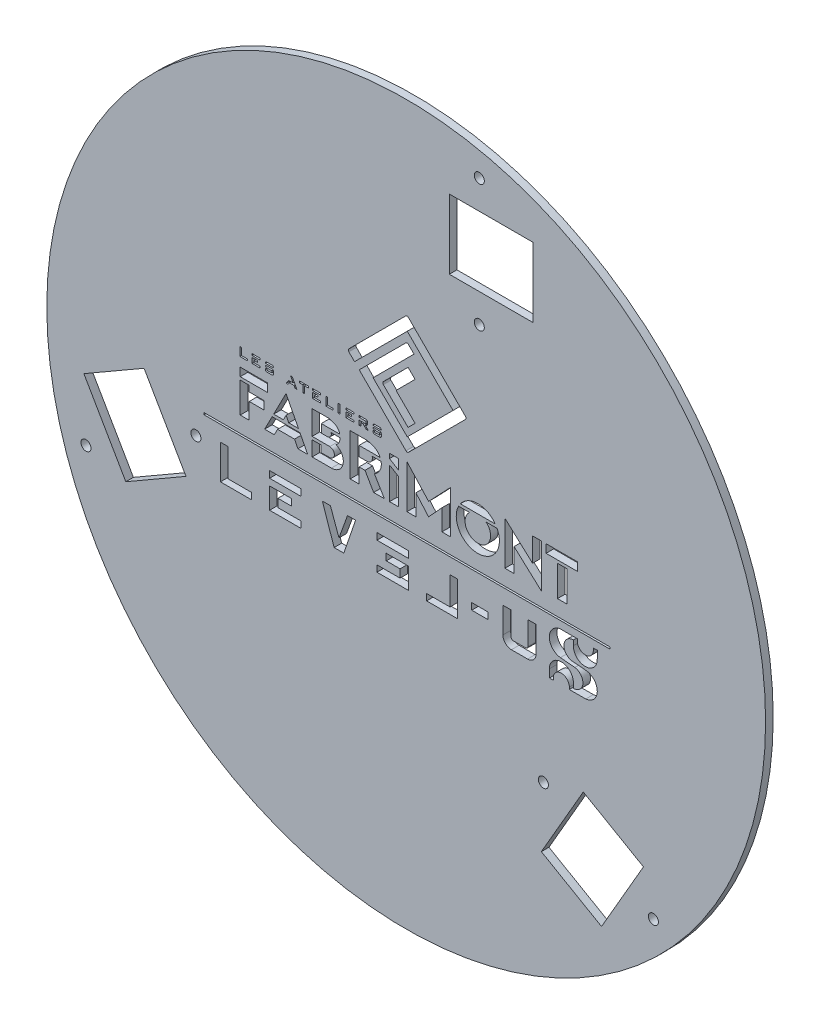
SolidWorks part; units mm, degrees
material "201 Acier inoxydable recuit (SS)"
ref_plane "Plan de face" through (0, 0, 0) normal (0, 0, 1) x (1, 0, 0)
ref_plane "Plan de dessus" through (0, 0, 0) normal (0, 1, 0) x (1, 0, 0)
ref_plane "Plan de droite" through (0, 0, 0) normal (1, 0, 0) x (0, 0, -1)
sketch "Esquisse1" plane through (0, 0, 0) normal (0, 0, 1) x (1, 0, 0)
  line B0 (39.8028, 108.2692) -> (61.818, 130.2872)
  line B1 (61.818, 130.2872) -> (80.9149, 111.1927)
  line B2 (86.1174, 111.6371) -> (62.256, 135.4954)
  circle B3 centre (61.368, 63.9273) radius 150
  line B4 (88.7074, 42.8985) -> (95.439, 42.8985)
  line B5 (95.439, 45.6563) -> (95.439, 42.8985)
  line B6 (88.7074, 45.6563) -> (95.439, 45.6563)
  line B7 (88.7074, 45.6563) -> (88.7074, 42.8985)
  line B8 (69.9017, 36.8558) -> (69.9017, 39.5372)
  line B9 (82.771, 36.8558) -> (69.9017, 36.8558)
  line B10 (82.771, 51.2103) -> (82.771, 36.8558)
  line B11 (79.6565, 51.2103) -> (82.771, 51.2103)
  line B12 (79.6565, 39.5372) -> (79.6565, 51.2103)
  line B13 (69.9017, 39.5372) -> (79.6565, 39.5372)
  line B14 (49.1501, 51.2103) -> (49.1501, 48.4256)
  line B15 (62.241, 48.4256) -> (49.1501, 48.4256)
  line B16 (62.241, 51.2103) -> (62.241, 48.4256)
  line B17 (62.241, 51.2103) -> (49.1501, 51.2103)
  line B18 (4.3716, 48.4256) -> (17.4625, 48.4256)
  line B19 (17.4625, 51.1933) -> (17.4625, 48.4256)
  line B20 (4.3716, 51.1933) -> (17.4625, 51.1933)
  line B21 (4.3716, 51.1933) -> (4.3716, 48.4256)
  line B22 (4.3716, 36.8558) -> (17.4625, 36.8558)
  line B23 (17.4625, 39.5291) -> (17.4625, 36.8558)
  line B24 (7.8145, 39.5291) -> (17.4625, 39.5291)
  line B25 (7.8145, 42.8985) -> (7.8145, 39.5291)
  line B26 (7.8145, 42.8985) -> (13.5765, 42.8985)
  line B27 (13.5765, 45.6563) -> (13.5765, 42.8985)
  line B28 (4.3716, 45.6563) -> (13.5765, 45.6563)
  line B29 (4.3716, 45.6563) -> (4.3716, 36.8558)
  line B30 (48.2118, 89.8237) -> (50.3046, 89.8237)
  line B31 (47.526, 89.1379) -> (47.526, 89.1275)
  line B32 (47.526, 89.1275) -> (50.9904, 89.1275)
  line B33 (50.9904, 89.1379) -> (50.9904, 89.1275)
  line B34 (36.2507, 89.8237) -> (36.2507, 89.1275)
  line B35 (39.5235, 89.1275) -> (36.2507, 89.1275)
  line B36 (39.5235, 89.8237) -> (39.5235, 89.1275)
  line B37 (36.2507, 89.8237) -> (39.5235, 89.8237)
  line B38 (27.7962, 86.2351) -> (30.9007, 86.2351)
  line B39 (30.9007, 86.9054) -> (30.9007, 86.2351)
  line B40 (28.4753, 86.9054) -> (30.9007, 86.9054)
  line B41 (28.4753, 89.8237) -> (28.4753, 86.9054)
  line B42 (27.7962, 89.8237) -> (28.4753, 89.8237)
  line B43 (27.7962, 89.8237) -> (27.7962, 86.2351)
  line B44 (32.9588, 86.2351) -> (33.6448, 86.2351)
  line B45 (33.6448, 89.8237) -> (33.6448, 86.2351)
  line B46 (32.9588, 89.8237) -> (33.6448, 89.8237)
  line B47 (32.9588, 89.8237) -> (32.9588, 86.2351)
  line B48 (24.5672, 88.4352) -> (24.5672, 87.7457)
  line B49 (22.266, 88.4352) -> (24.5672, 88.4352)
  line B50 (22.266, 88.4352) -> (22.266, 86.2351)
  line B51 (22.266, 86.2351) -> (25.5387, 86.2351)
  line B52 (25.5387, 86.9054) -> (25.5387, 86.2351)
  line B53 (23.1267, 86.9054) -> (25.5387, 86.9054)
  line B54 (23.1267, 87.7457) -> (23.1267, 86.9054)
  line B55 (23.1267, 87.7457) -> (24.5672, 87.7457)
  line B56 (22.266, 89.1275) -> (25.5387, 89.1275)
  line B57 (25.5387, 89.8237) -> (25.5387, 89.1275)
  line B58 (22.266, 89.8237) -> (25.5387, 89.8237)
  line B59 (22.266, 89.8237) -> (22.266, 89.1275)
  line B60 (-2.0636, 87.7457) -> (-0.6231, 87.7457)
  line B61 (-0.6231, 88.4352) -> (-0.6231, 87.7457)
  line B62 (-2.9243, 88.4352) -> (-0.6231, 88.4352)
  line B63 (-2.9243, 88.4352) -> (-2.9243, 86.2351)
  line B64 (-2.9243, 86.2351) -> (0.3484, 86.2351)
  line B65 (0.3484, 86.9034) -> (0.3484, 86.2351)
  line B66 (-2.0636, 86.9034) -> (0.3484, 86.9034)
  line B67 (-2.0636, 87.7457) -> (-2.0636, 86.9034)
  line B68 (-2.9243, 89.1275) -> (0.3484, 89.1275)
  line B69 (0.3484, 89.8237) -> (0.3484, 89.1275)
  line B70 (-2.9243, 89.8237) -> (0.3484, 89.8237)
  line B71 (-2.9243, 89.8237) -> (-2.9243, 89.1275)
  line B72 (62.1432, 95.6886) -> (51.8218, 105.9912)
  line B73 (65.0775, 98.6282) -> (62.1432, 95.6886)
  line B74 (57.1433, 106.5614) -> (65.0775, 98.6282)
  line B75 (65.0725, 114.505) -> (57.1433, 106.5614)
  line B76 (62.1527, 117.4195) -> (65.0725, 114.505)
  line B77 (51.8208, 107.0689) -> (62.1527, 117.4195)
  line B78 (3.2629, 86.2351) -> (5.3557, 86.2351)
  line B79 (6.0415, 87.7494) -> (6.0415, 86.9209)
  line B80 (2.5771, 88.4352) -> (5.3557, 88.4352)
  line B81 (2.5771, 88.4352) -> (2.5771, 88.4315)
  line B82 (3.2629, 87.7457) -> (5.3557, 87.7457)
  line B83 (5.3557, 87.7457) -> (5.3557, 86.9034)
  line B84 (3.2653, 86.9034) -> (5.3557, 86.9034)
  line B85 (3.2653, 87.3351) -> (3.2653, 86.9034)
  line B86 (2.5771, 87.3351) -> (3.2653, 87.3351)
  line B87 (2.5771, 86.9209) -> (2.5771, 87.3351)
  line B88 (20.5559, 89.8237) -> (20.5559, 89.1275)
  line B89 (16.7521, 89.8237) -> (20.5559, 89.8237)
  line B90 (16.7521, 89.8237) -> (16.7521, 89.1275)
  line B91 (16.7521, 89.1275) -> (18.2994, 89.1275)
  line B92 (18.2994, 89.1275) -> (18.2994, 86.2351)
  line B93 (18.2994, 86.2351) -> (18.9764, 86.2351)
  line B94 (18.9764, 89.1275) -> (18.9764, 86.2351)
  line B95 (18.9764, 89.1275) -> (20.5559, 89.1275)
  line B96 (54.4137, 80.5603) -> (58.1808, 78.2403)
  line B97 (58.1808, 78.2403) -> (58.1808, 82.4618)
  line B98 (54.4137, 82.4618) -> (58.1808, 82.4618)
  line B99 (54.4137, 82.4618) -> (54.4137, 80.5603)
  line B100 (65.4199, 73.6995) -> (65.4199, 64.9856)
  line B101 (70.7111, 67.6307) -> (65.4199, 73.6995)
  line B102 (76.2673, 73.6995) -> (70.7111, 67.6307)
  line B103 (76.2673, 64.9856) -> (76.2673, 73.6995)
  line B104 (79.8874, 64.9856) -> (76.2673, 64.9856)
  line B105 (79.8874, 82.8613) -> (79.8874, 64.9856)
  line B106 (70.7197, 73.2332) -> (79.8874, 82.8613)
  line B107 (61.6887, 83.0856) -> (70.7197, 73.2332)
  line B108 (61.6887, 64.9856) -> (61.6887, 83.0856)
  line B109 (61.6887, 64.9856) -> (65.4199, 64.9856)
  line B110 (94.707, 77.7674) -> (99.3064, 77.7674)
  line B111 (83.2222, 77.7674) -> (87.8216, 77.7674)
  line B112 (-23.0062, 57.679) -> (146.3836, 57.679)
  line B113 (146.3836, 58.4778) -> (146.3836, 57.679)
  line B114 (-23.0062, 58.4778) -> (146.3836, 58.4778)
  line B115 (-23.0062, 58.4778) -> (-23.0062, 57.679)
  line B116 (124.5042, 64.9856) -> (128.4237, 64.9856)
  line B117 (128.4237, 77.7674) -> (128.4237, 64.9856)
  line B118 (124.5042, 77.7674) -> (128.4237, 77.7674)
  line B119 (124.5042, 64.9856) -> (124.5042, 77.7674)
  line B120 (119.7421, 78.9781) -> (132.9293, 78.9781)
  line B121 (132.9293, 78.9781) -> (132.9293, 82.4618)
  line B122 (119.7421, 82.4618) -> (132.9293, 82.4618)
  line B123 (119.7421, 82.4618) -> (119.7421, 78.9781)
  line B124 (11.2269, 82.4618) -> (16.4081, 72.4291)
  line B125 (6.0539, 72.4291) -> (11.2269, 82.4618)
  line B126 (6.0539, 72.4291) -> (10.1027, 72.4291)
  line B127 (11.2269, 74.6095) -> (10.1027, 72.4291)
  line B128 (12.3529, 72.4291) -> (11.2269, 74.6095)
  line B129 (12.3529, 72.4291) -> (16.4081, 72.4291)
  line B130 (2.0157, 71.9118) -> (-4.1611, 71.9118)
  line B131 (2.0157, 75.3461) -> (2.0157, 71.9118)
  line B132 (-4.1611, 75.3461) -> (2.0157, 75.3461)
  line B133 (-4.1611, 77.7674) -> (-4.1611, 75.3461)
  line B134 (-7.9167, 77.7674) -> (-4.1611, 77.7674)
  line B135 (-7.9167, 65.1187) -> (-7.9167, 77.7674)
  line B136 (-4.1611, 65.1187) -> (-7.9167, 65.1187)
  line B137 (-4.1611, 71.9118) -> (-4.1611, 65.1187)
  line B138 (47.526, 88.4352) -> (50.3046, 88.4352)
  line B139 (47.526, 88.4352) -> (47.526, 88.4315)
  line B140 (48.2118, 87.7457) -> (50.3046, 87.7457)
  line B141 (50.3046, 87.7457) -> (50.3046, 86.9034)
  line B142 (48.2142, 86.9034) -> (50.3046, 86.9034)
  line B143 (48.2142, 87.3351) -> (48.2142, 86.9034)
  line B144 (47.526, 87.3351) -> (48.2142, 87.3351)
  line B145 (47.526, 86.9209) -> (47.526, 87.3351)
  line B146 (48.2118, 86.2351) -> (50.3046, 86.2351)
  line B147 (50.9904, 87.7494) -> (50.9904, 86.9209)
  line B148 (2.2846, 65.1187) -> (6.3334, 65.1187)
  line B149 (7.6996, 67.7684) -> (6.3334, 65.1187)
  line B150 (7.6996, 67.7684) -> (14.7598, 67.7684)
  line B151 (16.1969, 64.9856) -> (14.7598, 67.7684)
  line B152 (20.2521, 64.9856) -> (16.1969, 64.9856)
  line B153 (17.0426, 71.2005) -> (20.2521, 64.9856)
  line B154 (5.4205, 71.2005) -> (17.0426, 71.2005)
  line B155 (2.2846, 65.1187) -> (5.4205, 71.2005)
  line B156 (25.9311, 78.9782) -> (33.6797, 78.9782)
  line B157 (30.831, 81.9696) -> (29.2994, 82.4619)
  line B158 (22.1049, 82.4619) -> (29.2994, 82.4619)
  line B159 (22.1049, 82.4619) -> (22.1049, 72.4292)
  line B160 (22.1049, 72.4292) -> (29.4781, 72.4292)
  line B161 (25.9038, 68.4321) -> (29.3823, 68.4321)
  line B162 (25.9038, 71.2006) -> (25.9038, 68.4321)
  line B163 (22.1049, 71.2006) -> (25.9038, 71.2006)
  line B164 (22.1049, 71.2006) -> (22.1049, 64.9857)
  line B165 (22.1049, 64.9857) -> (30.1503, 64.9857)
  line B166 (30.0311, 77.7675) -> (33.8261, 77.7675)
  line B167 (25.9311, 75.5023) -> (28.6488, 75.5023)
  line B168 (25.9311, 78.9782) -> (25.9311, 75.5023)
  line B169 (41.7054, 78.9781) -> (50.4924, 78.9781)
  line B170 (47.1354, 81.9098) -> (45.198, 82.4618)
  line B171 (37.9796, 82.4618) -> (45.198, 82.4618)
  line B172 (37.9796, 82.4618) -> (37.9796, 64.9856)
  line B173 (37.9796, 64.9856) -> (41.7054, 64.9856)
  line B174 (41.7054, 64.9856) -> (41.7054, 71.2005)
  line B175 (41.7054, 71.2005) -> (44.1723, 71.2005)
  line B176 (44.1723, 71.2005) -> (47.7793, 64.9856)
  line B177 (47.7793, 64.9856) -> (52.2442, 64.9856)
  line B178 (52.2442, 64.9856) -> (48.0671, 71.9455)
  line B179 (47.1354, 77.7675) -> (50.8798, 77.7675)
  line B180 (41.7054, 74.8449) -> (45.0294, 74.8449)
  line B181 (41.7054, 78.9781) -> (41.7054, 74.8449)
  line B182 (-73.1498, 47.4625) -> (-55.6498, 17.1516)
  line B183 (-55.6498, 17.1516) -> (-30.5351, 31.6516)
  line B184 (-30.5351, 31.6516) -> (-48.0351, 61.9625)
  line B185 (-48.0351, 61.9625) -> (-73.1498, 47.4625)
  line B186 (135.271, 0.4747) -> (117.771, -29.8362)
  line B187 (117.771, -29.8362) -> (142.8858, -44.3362)
  line B188 (142.8858, -44.3362) -> (160.3858, -14.0253)
  line B189 (160.3858, -14.0253) -> (135.271, 0.4747)
  line B190 (79.368, 159.6555) -> (114.368, 159.6555)
  line B191 (114.368, 159.6555) -> (114.368, 188.6555)
  line B192 (114.368, 188.6555) -> (79.368, 188.6555)
  line B193 (79.368, 188.6555) -> (79.368, 159.6555)
  line B194 (61.2027, 125.7562) -> (41.7606, 106.3116)
  line B195 (61.2791, 86.7956) -> (41.7606, 106.3116)
  line B196 (62.3568, 86.7957) -> (86.1175, 110.5594)
  line B197 (37.4177, 111.7316) -> (61.1784, 135.4953)
  line B198 (39.8028, 108.2692) -> (37.4178, 110.6539)
  line B199 (80.9149, 111.1927) -> (61.818, 92.0934)
  line B200 (61.818, 92.0934) -> (47.5628, 106.3468)
  line B201 (47.5628, 106.3468) -> (64.6253, 123.4115)
  line B202 (64.6253, 123.4115) -> (62.2803, 125.7562)
  line B203 (54.4137, 64.9856) -> (58.1808, 64.9856)
  line B204 (58.1808, 75.9434) -> (58.1808, 64.9856)
  line B205 (54.4137, 78.2403) -> (58.1808, 75.9434)
  line B206 (54.4137, 78.2403) -> (54.4137, 64.9856)
  line B207 (3.4734, 82.4618) -> (-7.9167, 82.4618)
  line B208 (-7.9167, 82.4618) -> (-7.9167, 78.9781)
  line B209 (-7.9167, 78.9781) -> (3.4734, 78.9781)
  line B210 (3.4734, 78.9781) -> (3.4734, 82.4618)
  line B211 (102.5461, 64.9856) -> (106.3956, 64.9856)
  line B212 (106.3956, 74.7482) -> (106.3956, 64.9856)
  line B213 (117.8763, 64.2748) -> (106.3956, 74.7482)
  line B214 (117.8763, 82.4618) -> (117.8763, 64.2748)
  line B215 (114.108, 82.4618) -> (117.8763, 82.4618)
  line B216 (114.108, 82.4618) -> (114.108, 72.5572)
  line B217 (114.108, 72.5572) -> (102.5461, 83.0856)
  line B218 (102.5461, 83.0856) -> (102.5461, 64.9856)
  line B219 (83.9595, 78.9781) -> (98.5691, 78.9781)
  line B220 (14.5348, 87.0641) -> (14.9597, 86.2351)
  line B221 (14.9597, 86.2351) -> (15.7483, 86.2351)
  line B222 (13.8053, 89.8237) -> (15.7483, 86.2351)
  line B223 (13.1204, 89.8237) -> (13.8053, 89.8237)
  line B224 (13.1204, 89.8237) -> (14.1854, 87.7457)
  line B225 (12.2814, 87.7457) -> (14.1854, 87.7457)
  line B226 (11.3422, 86.2351) -> (12.2814, 87.7457)
  line B227 (11.3422, 86.2351) -> (12.0777, 86.2351)
  line B228 (12.0777, 86.2351) -> (12.5628, 87.0641)
  line B229 (12.5628, 87.0641) -> (14.5348, 87.0641)
  line B230 (3.2629, 89.8237) -> (5.3557, 89.8237)
  line B231 (2.5771, 89.1379) -> (2.5771, 89.1275)
  line B232 (2.5771, 89.1275) -> (6.0415, 89.1275)
  line B233 (-7.2782, 89.8237) -> (-8.0568, 89.8237)
  line B234 (-8.0568, 89.8237) -> (-8.0568, 86.2351)
  line B235 (-8.0568, 86.2351) -> (-4.8395, 86.2351)
  line B236 (-4.8395, 86.2351) -> (-4.8395, 86.9054)
  line B237 (-4.8395, 86.9054) -> (-7.2782, 86.9054)
  line B238 (-7.2782, 86.9054) -> (-7.2782, 89.8237)
  line B239 (36.2507, 86.2351) -> (39.5235, 86.2351)
  line B240 (39.5235, 86.9054) -> (39.5235, 86.2351)
  line B241 (37.1115, 86.9054) -> (39.5235, 86.9054)
  line B242 (37.1115, 87.7457) -> (37.1115, 86.9054)
  line B243 (37.1115, 87.7457) -> (38.552, 87.7457)
  line B244 (38.552, 88.4352) -> (38.552, 87.7457)
  line B245 (36.2507, 88.4352) -> (38.552, 88.4352)
  line B246 (36.2507, 88.4352) -> (36.2507, 86.2351)
  line B247 (45.1742, 89.1379) -> (45.1742, 88.2688)
  line B248 (41.7675, 89.8237) -> (44.4884, 89.8237)
  line B249 (41.7675, 89.8237) -> (41.7675, 89.1275)
  line B250 (41.7675, 89.1275) -> (44.51, 89.1275)
  line B251 (44.51, 89.1275) -> (44.51, 88.1035)
  line B252 (41.7675, 88.1035) -> (44.51, 88.1035)
  line B253 (41.7675, 88.1035) -> (41.7675, 86.2351)
  line B254 (41.7675, 86.2351) -> (42.5631, 86.2351)
  line B255 (42.5631, 86.2351) -> (42.5631, 87.5734)
  line B256 (42.5631, 87.5734) -> (43.3631, 87.5734)
  line B257 (43.3631, 87.5734) -> (44.6642, 86.2351)
  line B258 (44.6642, 86.2351) -> (45.6087, 86.2351)
  line B259 (44.2011, 87.583) -> (45.6087, 86.2351)
  line B260 (44.2011, 87.583) -> (44.4884, 87.583)
  line B261 (31.2817, 36.8388) -> (35.3306, 36.8388)
  line B262 (40.235, 51.1933) -> (35.3306, 36.8388)
  line B263 (40.235, 51.1933) -> (36.8744, 51.1933)
  line B264 (36.8744, 51.1933) -> (33.3061, 41.3238)
  line B265 (29.7378, 51.1933) -> (33.3061, 41.3238)
  line B266 (26.3773, 51.1933) -> (29.7378, 51.1933)
  line B267 (26.3773, 51.1933) -> (31.2817, 36.8388)
  line B268 (-3.2891, 39.5372) -> (-13.0439, 39.5372)
  line B269 (-13.0439, 39.5372) -> (-13.0439, 51.2103)
  line B270 (-13.0439, 51.2103) -> (-16.1585, 51.2103)
  line B271 (-16.1585, 51.2103) -> (-16.1585, 36.8558)
  line B272 (-16.1585, 36.8558) -> (-3.2891, 36.8558)
  line B273 (-3.2891, 36.8558) -> (-3.2891, 39.5372)
  line B274 (49.1501, 39.5291) -> (49.1501, 36.8558)
  line B275 (62.241, 36.8558) -> (49.1501, 36.8558)
  line B276 (62.241, 45.6563) -> (62.241, 36.8558)
  line B277 (62.241, 45.6563) -> (53.0361, 45.6563)
  line B278 (53.0361, 45.6563) -> (53.0361, 42.8985)
  line B279 (58.7981, 42.8985) -> (53.0361, 42.8985)
  line B280 (58.7981, 42.8985) -> (58.7981, 39.5291)
  line B281 (58.7981, 39.5291) -> (49.1501, 39.5291)
  line B282 (115.5796, 40.4674) -> (115.5796, 51.2103)
  line B283 (115.5796, 51.2103) -> (112.2191, 51.2103)
  line B284 (112.2191, 51.2103) -> (112.2191, 41.5374)
  line B285 (111.2031, 40.5214) -> (106.0985, 40.5214)
  line B286 (105.0825, 51.2103) -> (105.0825, 41.5374)
  line B287 (101.7219, 51.2103) -> (105.0825, 51.2103)
  line B288 (101.7219, 51.2103) -> (101.7219, 40.4674)
  line B289 (105.2779, 36.9114) -> (112.0236, 36.9114)
  line B290 (121.1489, 34.6087) -> (121.1197, 37.9245)
  line B291 (122.7583, 34.6087) -> (121.1489, 34.6087)
  line B292 (122.7583, 35.4712) -> (122.7583, 34.6087)
  line B293 (129.4604, 35.4712) -> (129.4604, 34.6087)
  line B294 (136.3117, 34.6087) -> (129.4604, 34.6087)
  line B295 (130.5575, 45.4514) -> (136.1173, 45.0077)
  line B296 (131.1263, 53.3642) -> (131.1165, 51.2484)
  line B297 (141.1491, 54.6249) -> (141.0994, 51.2484)
  line B298 (141.1491, 54.6249) -> (139.4593, 54.6249)
  line B299 (139.4593, 53.784) -> (139.4593, 54.6249)
  line B300 (132.7753, 53.784) -> (132.7753, 54.6249)
  line B301 (132.7753, 54.6249) -> (125.6999, 54.6249)
  line B302 (125.6999, 44.2672) -> (131.7548, 43.7322)
  line B303 (131.1263, 35.8751) -> (131.1495, 37.9245)
  arc B304 (-24.2928, 48.4769) -> (-28.4928, 48.4769) centre (-26.3928, 48.4769) ccw
  arc B305 (-28.4928, 48.4769) -> (-24.2928, 48.4769) centre (-26.3928, 48.4769) ccw
  arc B306 (-70.1921, 21.9769) -> (-74.3921, 21.9769) centre (-72.2921, 21.9769) ccw
  arc B307 (-74.3921, 21.9769) -> (-70.1921, 21.9769) centre (-72.2921, 21.9769) ccw
  arc B308 (120.7287, -4.3506) -> (116.5287, -4.3506) centre (118.6287, -4.3506) ccw
  arc B309 (116.5287, -4.3506) -> (120.7287, -4.3506) centre (118.6287, -4.3506) ccw
  arc B310 (166.6281, -30.8506) -> (162.4281, -30.8506) centre (164.5281, -30.8506) ccw
  arc B311 (162.4281, -30.8506) -> (166.6281, -30.8506) centre (164.5281, -30.8506) ccw
  arc B312 (89.768, 147.6555) -> (93.968, 147.6555) centre (91.868, 147.6555) ccw
  arc B313 (93.968, 147.6555) -> (89.768, 147.6555) centre (91.868, 147.6555) ccw
  arc B314 (93.968, 200.6555) -> (89.768, 200.6555) centre (91.868, 200.6555) ccw
  arc B315 (89.768, 200.6555) -> (93.968, 200.6555) centre (91.868, 200.6555) ccw
  arc B316 (48.2118, 89.8237) -> (47.526, 89.1379) centre (48.2118, 89.1379) ccw
  arc B317 (50.9904, 89.1379) -> (50.3046, 89.8237) centre (50.3046, 89.1379) ccw
  arc B318 (51.8208, 107.0689) -> (51.8218, 105.9912) centre (52.3601, 106.5305) ccw
  arc B319 (5.3557, 86.2351) -> (6.0415, 86.9209) centre (5.3557, 86.9209) ccw
  arc B320 (6.0415, 87.7494) -> (5.3557, 88.4352) centre (5.3557, 87.7494) ccw
  arc B321 (2.5771, 88.4315) -> (3.2629, 87.7457) centre (3.2629, 88.4315) ccw
  arc B322 (2.5771, 86.9209) -> (3.2629, 86.2351) centre (3.2629, 86.9209) ccw
  arc B323 (87.8216, 77.7674) -> (94.707, 77.7674) centre (91.2643, 73.6995) ccw
  arc B324 (83.2222, 77.7674) -> (99.3064, 77.7674) centre (91.2643, 73.6995) ccw
  arc B325 (47.526, 88.4315) -> (48.2118, 87.7457) centre (48.2118, 88.4315) ccw
  arc B326 (47.526, 86.9209) -> (48.2118, 86.2351) centre (48.2118, 86.9209) ccw
  arc B327 (50.3046, 86.2351) -> (50.9904, 86.9209) centre (50.3046, 86.9209) ccw
  arc B328 (50.9904, 87.7494) -> (50.3046, 88.4352) centre (50.3046, 87.7494) ccw
  arc B329 (33.6797, 78.9782) -> (30.831, 81.9696) centre (29.5101, 77.8597) ccw
  arc B330 (29.3823, 68.4321) -> (29.4781, 72.4292) centre (29.3823, 70.4318) ccw
  arc B331 (30.1503, 64.9857) -> (32.1241, 74.4241) centre (30.2166, 69.8974) ccw
  arc B332 (32.1241, 74.4241) -> (33.8261, 77.7675) centre (29.5101, 77.8597) ccw
  arc B333 (28.6488, 75.5023) -> (30.0311, 77.7675) centre (28.3824, 77.2192) ccw
  arc B334 (50.4924, 78.9781) -> (47.1354, 81.9098) centre (45.578, 76.7384) ccw
  arc B335 (48.0671, 71.9455) -> (50.8798, 77.7675) centre (45.578, 76.7384) ccw
  arc B336 (45.0294, 74.8449) -> (47.1354, 77.7675) centre (45.0294, 77.065) ccw
  arc B337 (162.4281, -30.8506) -> (166.6281, -30.8506) centre (164.5281, -30.8506) ccw
  arc B338 (89.768, 147.6555) -> (93.968, 147.6555) centre (91.868, 147.6555) ccw
  arc B339 (89.768, 200.6555) -> (93.968, 200.6555) centre (91.868, 200.6555) ccw
  arc B340 (-28.4928, 48.4769) -> (-24.2928, 48.4769) centre (-26.3928, 48.4769) ccw
  arc B341 (116.5287, -4.3506) -> (120.7287, -4.3506) centre (118.6287, -4.3506) ccw
  arc B342 (-74.3921, 21.9769) -> (-70.1921, 21.9769) centre (-72.2921, 21.9769) ccw
  arc B343 (211.368, 63.9273) -> (-88.632, 63.9273) centre (61.368, 63.9273) ccw
  arc B344 (62.2803, 125.7562) -> (61.2027, 125.7562) centre (61.7415, 125.2174) ccw
  arc B345 (61.2791, 86.7956) -> (62.3568, 86.7957) centre (61.8179, 87.3345) ccw
  arc B346 (86.1175, 110.5594) -> (86.1174, 111.6371) centre (85.5786, 111.0982) ccw
  arc B347 (62.256, 135.4954) -> (61.1784, 135.4953) centre (61.7172, 134.9566) ccw
  arc B348 (37.4177, 111.7316) -> (37.4178, 110.6539) centre (37.9565, 111.1928) ccw
  arc B349 (98.5691, 78.9781) -> (83.9595, 78.9781) centre (91.2643, 73.6995) ccw
  arc B350 (6.0415, 89.1275) -> (5.3557, 89.8237) centre (5.3558, 89.1379) ccw
  arc B351 (3.2629, 89.8237) -> (2.5771, 89.1379) centre (3.2629, 89.1379) ccw
  arc B352 (44.4884, 87.583) -> (45.1742, 88.2688) centre (44.4884, 88.2688) ccw
  arc B353 (45.1742, 89.1379) -> (44.4884, 89.8237) centre (44.4884, 89.1379) ccw
  arc B354 (112.0236, 36.9114) -> (115.5796, 40.4674) centre (112.0236, 40.4674) ccw
  arc B355 (111.2031, 40.5214) -> (112.2191, 41.5374) centre (111.2031, 41.5374) ccw
  arc B356 (105.0825, 41.5374) -> (106.0985, 40.5214) centre (106.0985, 41.5374) ccw
  arc B357 (101.7219, 40.4674) -> (105.2779, 36.9114) centre (105.2779, 40.4674) ccw
  arc B358 (131.1495, 37.9245) -> (121.1197, 37.9245) centre (126.1346, 37.9245) ccw
  arc B359 (129.4604, 35.4712) -> (122.7583, 35.4712) centre (126.1093, 35.4712) ccw
  arc B360 (136.3117, 34.6087) -> (136.1173, 45.0077) centre (135.9033, 39.8024) ccw
  arc B361 (131.1263, 53.3642) -> (130.5575, 45.4514) centre (131.1938, 49.3825) ccw
  arc B362 (131.1165, 51.2484) -> (141.0994, 51.2484) centre (136.1079, 51.2484) ccw
  arc B363 (132.7753, 53.784) -> (139.4593, 53.784) centre (136.1173, 53.784) ccw
  arc B364 (125.6999, 54.6249) -> (125.6999, 44.2672) centre (126.3061, 49.4461) ccw
  arc B365 (131.1263, 35.8751) -> (131.7548, 43.7322) centre (131.177, 39.8247) ccw
sketch_block_instance "Base_ (1)-1"
sketch_block "Base_ (1)"
other "Objet de détail2"
extrude "Boss.-Extru.1" add sketch "Esquisse1" along normal blind 3.175 contours B3 B357 B288 B287 B286 B356 B285 B355 B284 B283 B282 B354 B289 B353 B247 B352 B260 B259 B258 B257 B256 B255 B254 B253 B252 B251 B250 B249 B248 B351 B230 B350 B232 B231 B349 B219 B348 B197 B347 B2 B346 B196 B345 B195 B194
